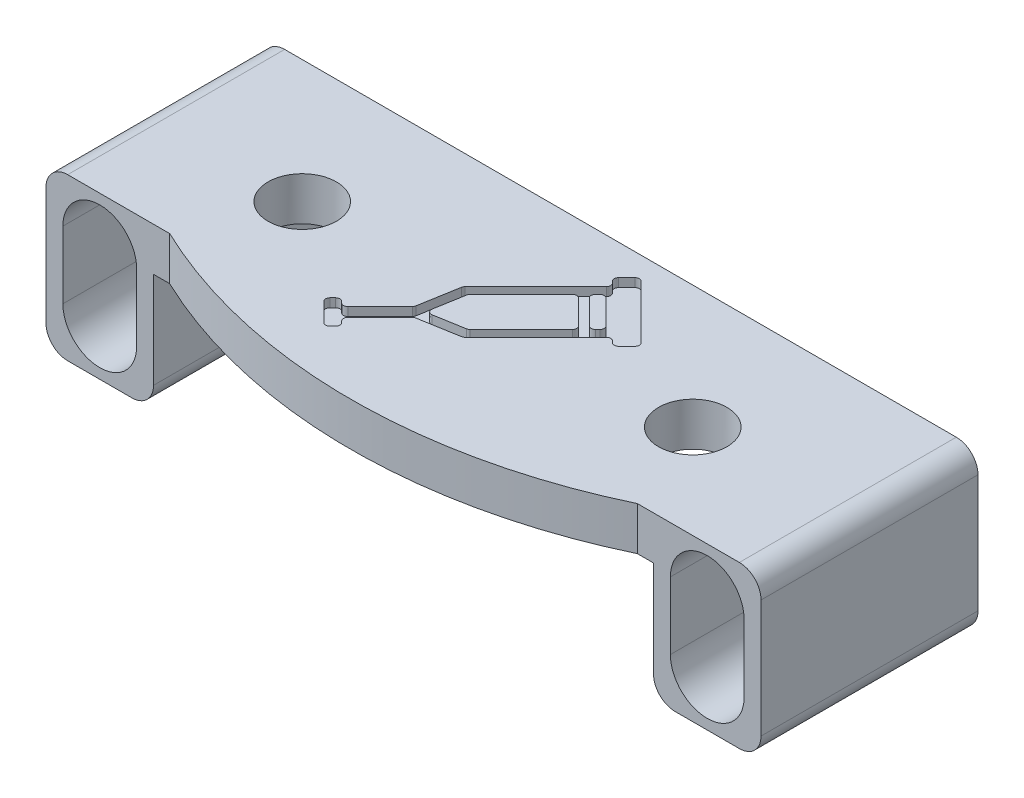
SolidWorks part; units mm, degrees
ref_plane "Спереди" through (0, 0, 0) normal (0, 0, 1) x (1, 0, 0)
ref_plane "Сверху" through (0, 0, 0) normal (0, 1, 0) x (1, 0, 0)
ref_plane "Справа" through (0, 0, 0) normal (1, 0, 0) x (0, 0, -1)
sketch "Эскиз1" plane through (0, 0, 0) normal (0, 1, 0) x (1, 0, 0)
  line L0 (-9, 0) -> (9, 0) construction
  line L2 (-13.5564, -4.7594) -> (13.5564, -4.7594)
  line L3 (-13.5564, -4.7594) -> (-13.5564, 4.7594)
  line L4 (-13.5564, 4.7594) -> (13.5564, 4.7594)
  line L5 (13.5564, -4.7594) -> (13.5564, 4.7594)
  line L6 (-13.5564, -4.7594) -> (13.5564, 4.7594) construction
  line L7 (-13.5564, 4.7594) -> (13.5564, -4.7594) construction
  circle A0 centre (-9, 0) radius 1.575
  circle A1 centre (9, 0) radius 1.575
  point P4 (0, 0)
  point P5 (0, 0)
  dimension "D2" = 3.15
  dimension "D3" = 3.15
  dimension "D1" = 18
extrude "Бобышка-Вытянуть1" add sketch "Эскиз1" along normal blind 2
sketch "Эскиз10" plane through (0, 0, 0) normal (0, 0, 1) x (1, 0, 0)
  line L4 (-15.7, -0.1653) -> (-15.7, -3.2653)
  line L5 (-12.3, -3.2653) -> (-12.3, -0.1653)
  line L18 (-11.5218, 0) -> (-3.3538, 0)
  line L19 (-3.3538, 0) -> (-3.3538, 2)
  line L20 (-3.3538, 2) -> (-11.5218, 2)
  line L21 (-11.5218, 2) -> (-16.4782, 2)
  line L22 (-16.4782, 2) -> (-16.4782, -5.4306)
  line L23 (-16.4782, -5.4306) -> (-11.5218, -5.4306)
  line L24 (-11.5218, -5.4306) -> (-11.5218, 0)
  arc A4 (-15.7, -3.2653) -> (-12.3, -3.2653) centre (-14, -3.2653) ccw
  arc A5 (-12.3, -0.1653) -> (-15.7, -0.1653) centre (-14, -0.1653) ccw
sketch "Эскиз2" plane through (0, 0, -4.7594) normal (0, 0, -1) x (-1, 0, 0)
  line L4 (-13.5564, 0) -> (13.5564, 0)
  line L5 (13.5564, 0) -> (13.5564, 2)
  line L6 (13.5564, 2) -> (-13.5564, 2)
  line L7 (-13.5564, 2) -> (-13.5564, 0)
  line L8 (-13.5564, 0) -> (13.5564, 0)
  line L9 (13.5564, 0) -> (13.5564, 2)
  line L10 (13.5564, 2) -> (-13.5564, 2)
  line L11 (-13.5564, 2) -> (-13.5564, 0)
  dimension "D1" = 0
extrude "Бобышка-Вытянуть2" add sketch "Эскиз2" along normal blind 0.91
sketch "Эскиз3" plane through (0, 0, 0) normal (0, -1, 0) x (1, 0, 0)
  line L0 (-3, 5.765) -> (-10.0436, 3.8615)
  line L1 (-9, 0) -> (9, 0) construction
  line L2 (0, 0) -> (0, 10.6755) construction
  line L3 (-3, -5.765) -> (-10.0436, -3.8615)
  line L4 (3, -5.765) -> (10.0436, -3.8615)
  line L5 (3, 5.765) -> (10.0436, 3.8615)
  line L6 (-3, 5.765) -> (-14.5564, 5.765)
  line L7 (-14.5564, 5.765) -> (-14.5564, -5.765)
  line L8 (-14.5564, -5.765) -> (-3, -5.765)
  line L9 (14.5564, -5.765) -> (3, -5.765)
  line L10 (14.5564, 5.765) -> (14.5564, -5.765)
  line L11 (3, 5.765) -> (14.5564, 5.765)
  circle A0 centre (-9, 0) radius 4
  circle A1 centre (9, 0) radius 4
  line M7 (13.5564, -5.6694) -> (13.5564, 4.7594)
  line M8 (13.5564, 4.7594) -> (-13.5564, 4.7594)
  line M9 (-13.5564, 4.7594) -> (-13.5564, -5.6694)
  line M10 (-13.5564, -5.6694) -> (13.5564, -5.6694)
  dimension "D1" = 8
  dimension "D2" = 8
extrude "Вырез-Вытянуть1" cut sketch "Эскиз3" against normal through all contours L7 L8 L3 L0 L6 M10 M9 M8 | A0 L0 L3 M8 M9 M10 | A1 L4 L5 M10 M7 M8 | L11 L5 L4 L9 L10 M8 M7 M10
sketch "Эскиз4" plane through (0, 0, -5.6694) normal (0, 0, -1) x (-1, 0, 0)
  line L0 (11.5218, 2) -> (11.5218, -6.403)
  line L1 (13, 2) -> (10.0436, 2) construction
  line L2 (11.5218, 2) -> (11.5218, 3.6861)
  line L3 (11.5218, 3.6861) -> (13.6183, 3.6861)
  line L4 (13.6183, 3.6861) -> (13.6183, -6.403)
  line L5 (13.6183, -6.403) -> (11.5218, -6.403)
  line L6 (0, 0) -> (0, 13.531) construction
  line L7 (-3.3538, 0) -> (3.3538, 0) construction
  line L8 (-13.6183, -6.403) -> (-11.5218, -6.403)
  line L9 (-13.6183, 3.6861) -> (-13.6183, -6.403)
  line L10 (-11.5218, 3.6861) -> (-13.6183, 3.6861)
  line L11 (-11.5218, 2) -> (-11.5218, 3.6861)
  line L12 (-11.5218, 2) -> (-11.5218, -6.403)
extrude "Вырез-Вытянуть2" cut sketch "Эскиз4" against normal through all
sketch "Эскиз5" plane through (0, 0, -5.6694) normal (0, 0, -1) x (-1, 0, 0)
  circle A0 centre (14, -0.6653) radius 1.7
sketch "Эскиз6" plane through (0, 0, -5.6694) normal (0, 0, -1) x (-1, 0, 0)
  circle A0 centre (14, -0.1653) radius 1.7
sketch "Эскиз7" plane through (0, 0, -5.6694) normal (0, 0, -1) x (-1, 0, 0)
  line L2 (15.7, -3.2653) -> (15.7, -0.1653)
  line L3 (12.3, -0.1653) -> (12.3, -3.2653)
  line L4 (15.7, -3.2653) -> (15.7, -0.1653)
  line L5 (12.3, -0.1653) -> (12.3, -3.2653)
  line L7 (3.3538, 0) -> (11.5218, 0)
  line L8 (3.3538, 2) -> (3.3538, 0)
  line L9 (11.5218, 2) -> (3.3538, 2)
  line L10 (16.4782, 2) -> (11.5218, 2)
  line L11 (16.4782, -5.4306) -> (16.4782, 2)
  line L12 (11.5218, -5.4306) -> (16.4782, -5.4306)
  line L13 (11.5218, 0) -> (11.5218, -5.4306)
  line L14 (3.3538, 0) -> (11.5218, 0)
  line L15 (3.3538, 2) -> (3.3538, 0)
  line L16 (11.5218, 2) -> (3.3538, 2)
  line L17 (16.4782, 2) -> (11.5218, 2)
  line L18 (16.4782, -5.4306) -> (16.4782, 2)
  line L19 (11.5218, -5.4306) -> (16.4782, -5.4306)
  line L20 (11.5218, 0) -> (11.5218, -5.4306)
  arc A2 (12.3, -3.2653) -> (15.7, -3.2653) centre (14, -3.2653) ccw
  arc A3 (15.7, -0.1653) -> (12.3, -0.1653) centre (14, -0.1653) ccw
  arc A4 (12.3, -3.2653) -> (15.7, -3.2653) centre (14, -3.2653) ccw
  arc A5 (15.7, -0.1653) -> (12.3, -0.1653) centre (14, -0.1653) ccw
  dimension "D1" = 0
  dimension "D2" = 0
extrude "Бобышка-Вытянуть3" add sketch "Эскиз7" against normal blind 10
sketch "Эскиз8" plane through (0, 2, 0) normal (0, 1, 0) x (1, 0, 0)
  circle A3 centre (-9, 0) radius 1.575
  circle A4 centre (-9, 0) radius 1.575
  dimension "D2" = 0
extrude "Вырез-Вытянуть3" cut sketch "Эскиз8" against normal blind 10
mirror "Зеркальное отражение1" about plane through (0, 0, 0) normal (1, 0, 0) of "Бобышка-Вытянуть3", "Вырез-Вытянуть3"
sketch "Эскиз9" plane through (0, 2, 0) normal (0, 1, 0) x (1, 0, 0)
  line L0 (-6.721, -4.7594) -> (6.721, -4.7594) construction
  line L1 (-6.721, -4.7594) -> (6.721, -4.7594)
  line L3 (-6.721, -4.7594) -> (-8.3077, -4.3306) construction
  line L5 (6.721, -4.7594) -> (8.3077, -4.3306) construction
  line L6 (-16.4782, -4.3306) -> (-8.3077, -4.3306)
  line L7 (-6.721, -4.7594) -> (-8.3077, -4.3306)
  line L8 (16.4782, -4.3306) -> (8.3077, -4.3306)
  line L9 (6.721, -4.7594) -> (8.3077, -4.3306)
  arc A0 (-10.8, -4.32) -> (10.8, -4.32) centre (0, 18.2268) ccw construction
  arc A1 (-10.8, -4.32) -> (10.8, -4.32) centre (0, 18.2268) ccw
extrude "Бобышка-Вытянуть4" add sketch "Эскиз9" against normal up to surface (2 mm away) up to face at (9, 0, -1.575)
fillet "Скругление2" radius 1 6 edges at (16.4782, 2, -0.6694) (16.4782, -5.4306, -0.6694) (11.5218, -5.4306, -0.6694) (-11.5218, -5.4306, -0.6694) (-16.4782, -5.4306, -0.6694) (-16.4782, 2, -0.6694)
sketch "Эскиз11" plane through (0, 2, 0) normal (0, 1, 0) x (1, 0, 0)
  line L0 (242.4448, 791.1856) -> (1242.4448, 791.1856) construction
sketch "Эскиз12" plane through (0, 2, 0) normal (0, 1, 0) x (1, 0, 0)
  line L0 (-4.0961, -3.9087) -> (3.2177, 3.405) construction
  line L1 (4.4466, 2.1761) -> (1.9888, 4.6339)
  line L2 (1.7059, 4.6339) -> (1.3274, 4.2554)
  line L3 (1.3274, 3.9725) -> (1.4028, 3.8971)
  line L4 (1.4028, 3.6143) -> (-1.8523, 0.3592)
  line L5 (-1.908, 0.2518) -> (-2.2184, -1.5463)
  line L6 (-2.274, -1.6537) -> (-3.7582, -3.138)
  line L7 (-4.0411, -3.138) -> (-4.1095, -3.0695)
  line L8 (-4.3923, -3.0695) -> (-4.5224, -3.1996)
  line L9 (-4.5224, -3.4824) -> (-3.6698, -4.335)
  line L10 (2.9638, 2.036) -> (1.8487, 3.1511)
  line L11 (1.5658, 3.1511) -> (1.4654, 3.0507)
  line L12 (1.4654, 2.7678) -> (2.5805, 1.6527)
  line L13 (2.3341, 1.4063) -> (1.2189, 2.5214)
  line L14 (0.9361, 2.5214) -> (-1.4243, 0.161)
  line L15 (-1.4799, 0.0536) -> (-1.7126, -1.2942)
  line L16 (-0.1337, -1.2926) -> (-1.4815, -1.5253)
  line L17 (2.3341, 1.1234) -> (-0.0263, -1.2369)
  line L18 (2.9638, 1.7532) -> (2.8633, 1.6527)
  line L19 (-3.2569, -4.205) -> (-3.3869, -4.335)
  line L20 (-3.3253, -3.8538) -> (-3.2569, -3.9222)
  line L21 (-1.8411, -2.0867) -> (-3.3253, -3.5709)
  line L22 (0.0644, -1.7206) -> (-1.7337, -2.031)
  line L23 (3.4269, 1.5901) -> (0.1718, -1.665)
  line L24 (3.7852, 1.5147) -> (3.7098, 1.5901)
  line L25 (4.4466, 1.8932) -> (4.068, 1.5147)
  arc A0 (-1.4243, 0.161) -> (-1.4799, 0.0536) centre (-1.2829, 0.0196) ccw
  arc A1 (-1.8523, 0.3592) -> (-1.908, 0.2518) centre (-1.7109, 0.2177) ccw
  arc A2 (-2.2184, -1.5463) -> (-2.274, -1.6537) centre (-2.4154, -1.5123) cw
  arc A3 (-3.7582, -3.138) -> (-4.0411, -3.138) centre (-3.8997, -2.9965) cw
  arc A4 (-4.5224, -3.1996) -> (-4.5224, -3.4824) centre (-4.381, -3.341) ccw
  arc A5 (-4.1095, -3.0695) -> (-4.3923, -3.0695) centre (-4.2509, -3.211) ccw
  arc A6 (1.2189, 2.5214) -> (0.9361, 2.5214) centre (1.0775, 2.38) ccw
  arc A7 (1.8487, 3.1511) -> (1.5658, 3.1511) centre (1.7072, 3.0097) ccw
  arc A8 (1.3274, 4.2554) -> (1.3274, 3.9725) centre (1.4688, 4.1139) ccw
  arc A9 (1.9888, 4.6339) -> (1.7059, 4.6339) centre (1.8473, 4.4925) ccw
  arc A10 (1.4654, 3.0507) -> (1.4654, 2.7678) centre (1.6068, 2.9092) ccw
  arc A11 (1.4028, 3.8971) -> (1.4028, 3.6143) centre (1.2614, 3.7557) cw
  arc A12 (3.7098, 1.5901) -> (3.4269, 1.5901) centre (3.5683, 1.4487) ccw
  arc A13 (2.8633, 1.6527) -> (2.5805, 1.6527) centre (2.7219, 1.7941) cw
  arc A14 (4.4466, 2.1761) -> (4.4466, 1.8932) centre (4.3051, 2.0347) cw
  arc A15 (4.068, 1.5147) -> (3.7852, 1.5147) centre (3.9266, 1.6561) cw
  arc A16 (2.9638, 2.036) -> (2.9638, 1.7532) centre (2.8224, 1.8946) cw
  arc A17 (2.3341, 1.4063) -> (2.3341, 1.1234) centre (2.1927, 1.2649) cw
  arc A18 (-3.2569, -3.9222) -> (-3.2569, -4.205) centre (-3.3983, -4.0636) cw
  arc A19 (-3.3869, -4.335) -> (-3.6698, -4.335) centre (-3.5283, -4.1936) cw
  arc A20 (-3.3253, -3.5709) -> (-3.3253, -3.8538) centre (-3.1839, -3.7123) ccw
  arc A21 (-1.7337, -2.031) -> (-1.8411, -2.0867) centre (-1.6996, -2.2281) ccw
  arc A22 (0.1718, -1.665) -> (0.0644, -1.7206) centre (0.0304, -1.5235) cw
  arc A23 (-0.0263, -1.2369) -> (-0.1337, -1.2926) centre (-0.1677, -1.0955) cw
  arc A24 (-1.7126, -1.2942) -> (-1.4815, -1.5253) centre (-1.5155, -1.3282) ccw
  point P12 (2.0229, 2.2103)
  point P14 (2.4062, 2.5936)
  point P78 (1.7765, 1.9638)
  point P80 (-1.7608, -1.5735)
  dimension "D1" = 0.2
  dimension "D2" = 0.2
extrude "Вырез-Вытянуть4" cut sketch "Эскиз12" against normal blind 0.4
